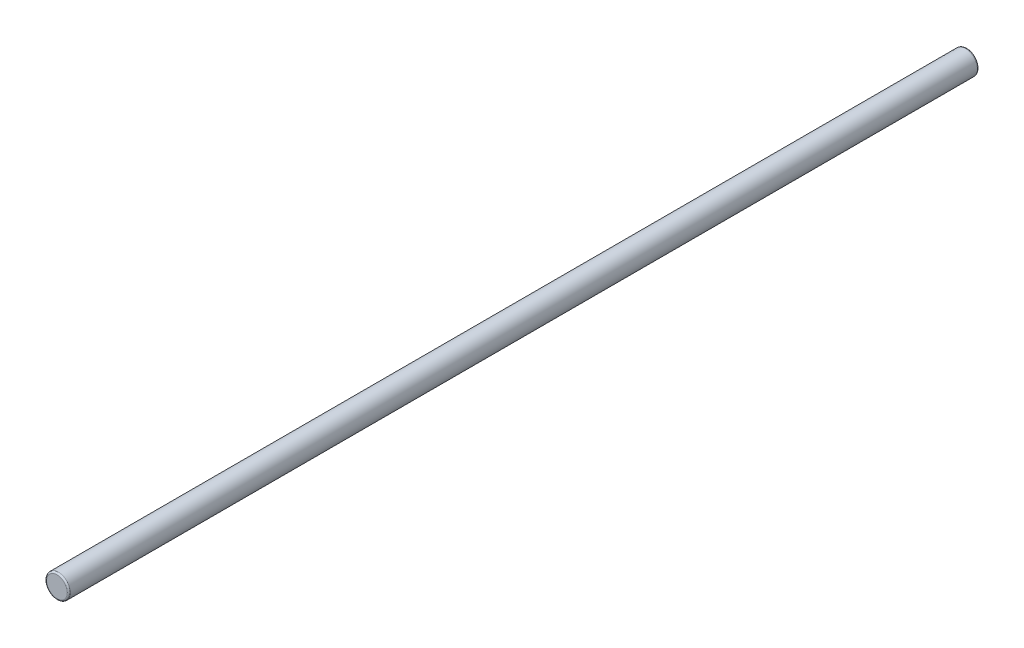
SolidWorks part; units mm, degrees
material "Pine"
ref_plane "Front Plane" through (0, 0, 0) normal (0, 0, 1) x (1, 0, 0)
ref_plane "Top Plane" through (0, 0, 0) normal (0, 1, 0) x (1, 0, 0)
ref_plane "Right Plane" through (0, 0, 0) normal (1, 0, 0) x (0, 0, -1)
sketch "Sketch1" plane through (0, 0, 0) normal (0, 0, 1) x (1, 0, 0)
  circle A0 centre (0, 0) radius 3.9688
  dimension "D1" = 7.9375
extrude "Extrude1" add sketch "Sketch1" against normal blind 304.8
fillet "Fillet1" radius 0.508 2 edges at (3.9688, 0, 0) (3.9688, 0, -304.8)
